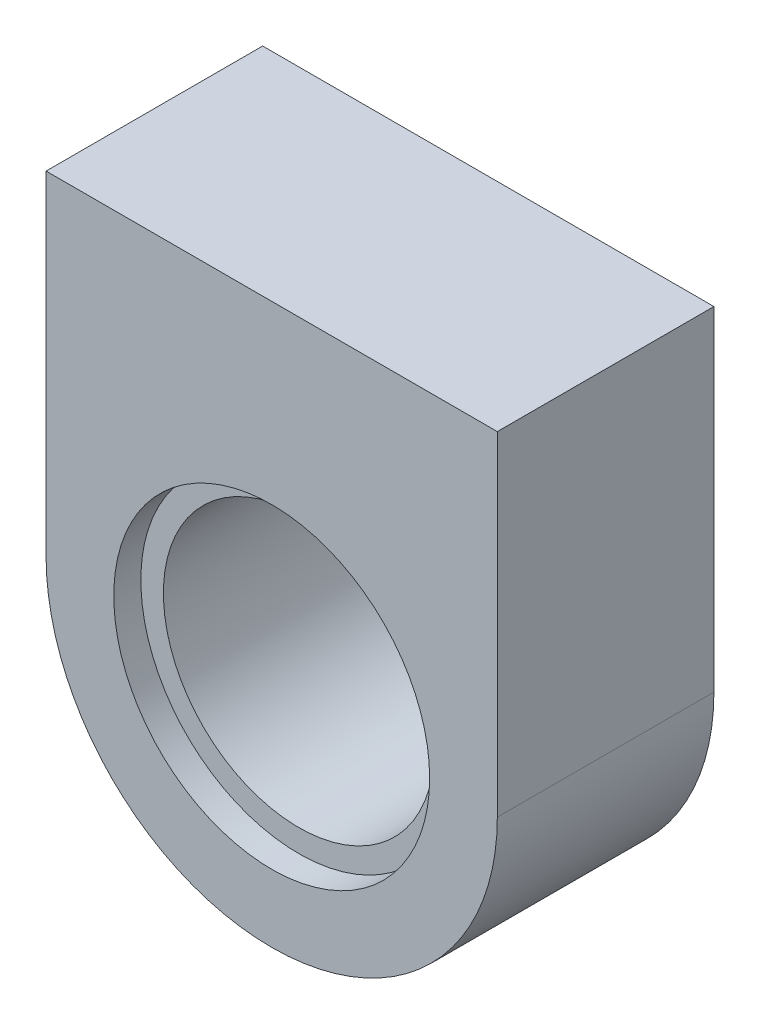
SolidWorks part; units mm, degrees
ref_plane "前视基准面" through (0, 0, 0) normal (0, 0, 1) x (1, 0, 0)
ref_plane "上视基准面" through (0, 0, 0) normal (0, 1, 0) x (1, 0, 0)
ref_plane "右视基准面" through (0, 0, 0) normal (1, 0, 0) x (0, 0, -1)
other "Configuration Table"
sketch "草图1" plane through (0, 0, 0) normal (0, 0, 1) x (1, 0, 0)
  line L0 (-25, 0) -> (-25, 37)
  line L1 (-25, 37) -> (25, 37)
  line L2 (25, 37) -> (25, 0)
  arc A0 (-25, 0) -> (25, 0) centre (0, 0) ccw
  dimension "D1" = 50
  dimension "D2" = 37
extrude "凸台-拉伸1" add sketch "草图1" along normal blind 24
sketch "草图2" plane through (0, 0, 24) normal (0, 0, 1) x (1, 0, 0)
  circle A0 centre (0, 0) radius 17.5
  dimension "D1" = 35
extrude "切除-拉伸1" cut sketch "草图2" against normal blind 3
sketch "草图3" plane through (0, 0, 21) normal (0, 0, 1) x (1, 0, 0)
  circle A0 centre (0, 0) radius 15
  dimension "D1" = 30
extrude "切除-拉伸2" cut sketch "草图3" against normal up to next
